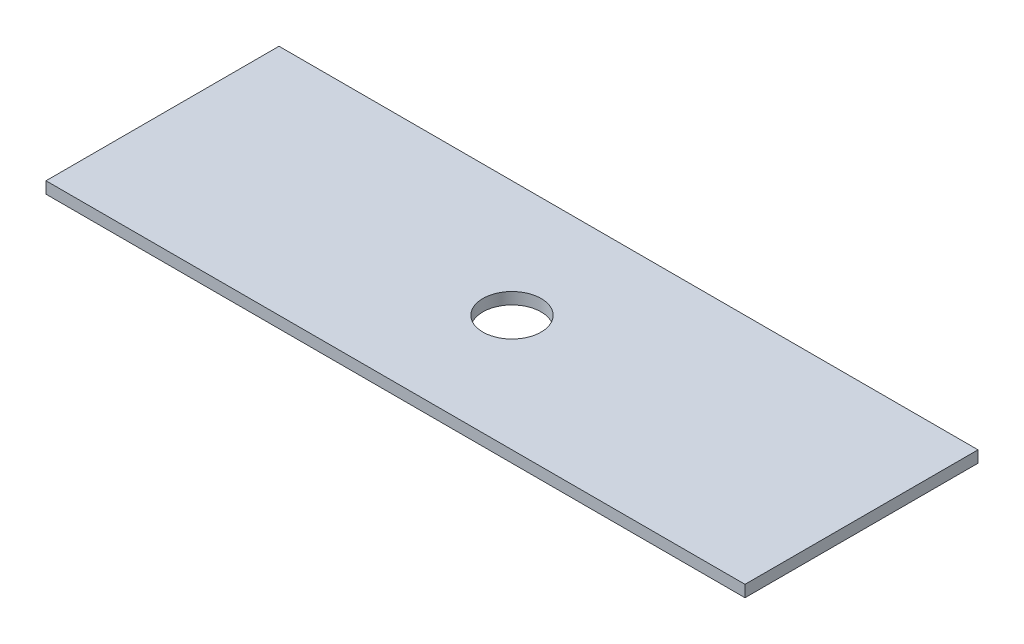
SolidWorks part; units mm, degrees
ref_plane "Front Plane" through (0, 0, 0) normal (0, 0, 1) x (1, 0, 0)
ref_plane "Top Plane" through (0, 0, 0) normal (0, 1, 0) x (1, 0, 0)
ref_plane "Right Plane" through (0, 0, 0) normal (1, 0, 0) x (0, 0, -1)
sketch "Sketch1" plane through (0, 0, 0) normal (0, 1, 0) x (1, 0, 0)
  line L1 (0, 0) -> (152.4, 0)
  line L2 (0, 0) -> (0, 50.8)
  line L3 (0, 50.8) -> (152.4, 50.8)
  line L4 (152.4, 0) -> (152.4, 50.8)
  circle A0 centre (76.2, 25.4) radius 6.35
  dimension "D3" = 12.7
  dimension "D1" = 152.4
  dimension "D2" = 50.8
  dimension "D4" = 76.2
  dimension "D5" = 25.4
extrude "Boss-Extrude1" add sketch "Sketch1" along normal blind 2.54
